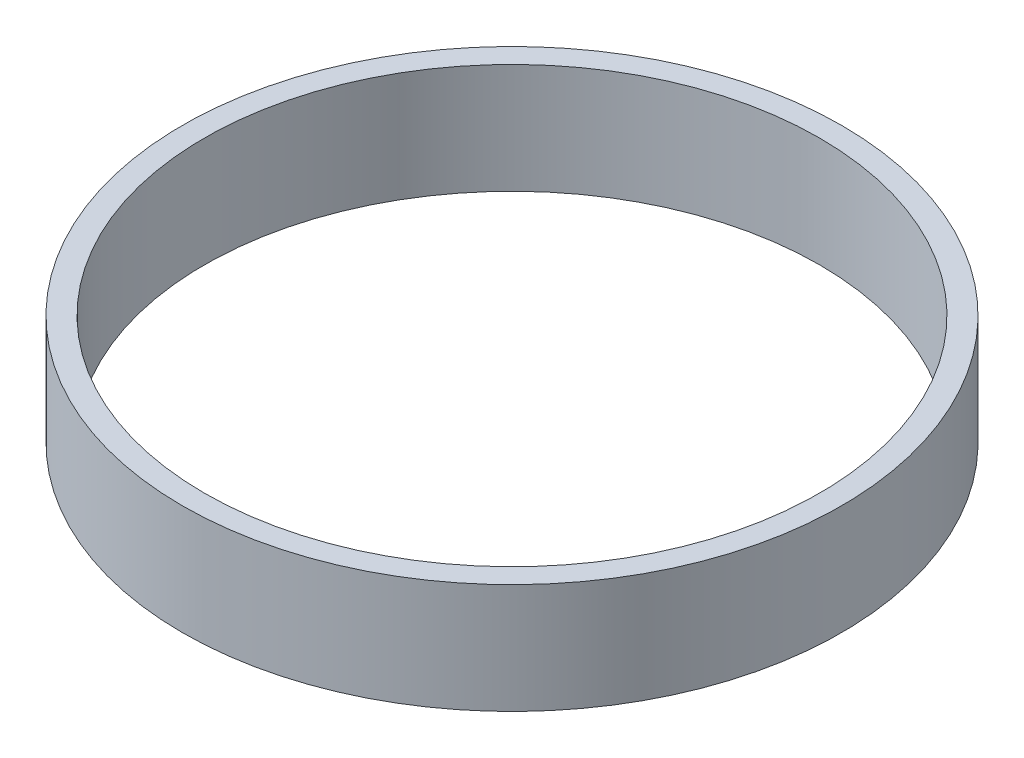
SolidWorks part; units mm, degrees
ref_plane "Front Plane" through (0, 0, 0) normal (0, 0, 1) x (1, 0, 0)
ref_plane "Top Plane" through (0, 0, 0) normal (0, 1, 0) x (1, 0, 0)
ref_plane "Right Plane" through (0, 0, 0) normal (1, 0, 0) x (0, 0, -1)
sketch "Sketch1" plane through (0, 0, 0) normal (0, 1, 0) x (1, 0, 0)
  circle A0 centre (0, 0) radius 28
  circle A1 centre (0, 0) radius 30
  dimension "D1" = 2
  dimension "D2" = 60
extrude "Boss-Extrude1" add sketch "Sketch1" along normal blind 10
